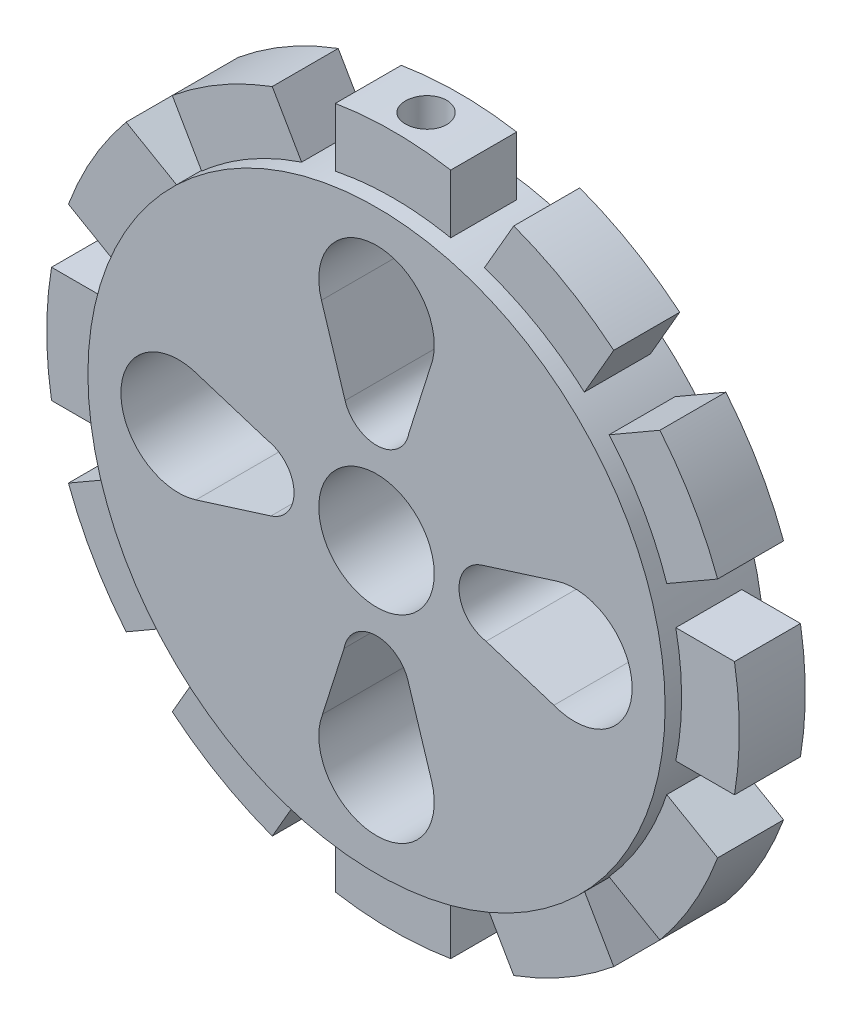
SolidWorks part; units mm, degrees
ref_plane "Alzado" through (0, 0, 0) normal (0, 0, 1) x (1, 0, 0)
ref_plane "Planta" through (0, 0, 0) normal (0, 1, 0) x (1, 0, 0)
ref_plane "Vista lateral" through (0, 0, 0) normal (1, 0, 0) x (0, 0, -1)
sketch "Croquis1" plane through (0, 0, 0) normal (0, 0, 1) x (1, 0, 0)
  line L0 (0, 50.5358) -> (0, -48.5678) construction
  line L1 (-51.7307, 0) -> (57.213, 0) construction
  line L2 (-6.6776, 21.9) -> (-3.8158, 12.8)
  line L3 (3.9355, 13.2848) -> (6.5412, 21.5075)
  line L4 (21.9, 6.6776) -> (12.8, 3.8158)
  line L5 (13.2848, -3.9355) -> (21.5075, -6.5412)
  line L6 (6.6776, -21.9) -> (3.8158, -12.8)
  line L7 (-3.9355, -13.2848) -> (-6.5412, -21.5075)
  line L8 (-21.9, -6.6776) -> (-12.8, -3.8158)
  line L9 (-13.2848, 3.9355) -> (-21.5075, 6.5412)
  circle A0 centre (0, 0) radius 7
  circle A1 centre (0, 0) radius 35
  arc A2 (-3.8158, 12.8) -> (3.9355, 13.2848) centre (0, 14) ccw
  arc A3 (6.5412, 21.5075) -> (-6.6776, 21.9) centre (0, 24) ccw
  arc A4 (21.5075, -6.5412) -> (21.9, 6.6776) centre (24, 0) ccw
  arc A5 (12.8, 3.8158) -> (13.2848, -3.9355) centre (14, 0) ccw
  arc A6 (-6.5412, -21.5075) -> (6.6776, -21.9) centre (0, -24) ccw
  arc A7 (3.8158, -12.8) -> (-3.9355, -13.2848) centre (0, -14) ccw
  arc A8 (-21.5075, 6.5412) -> (-21.9, -6.6776) centre (-24, 0) ccw
  arc A9 (-12.8, -3.8158) -> (-13.2848, 3.9355) centre (-14, 0) ccw
  point P43 (0, 0)
  dimension "D1" = 14
  dimension "D2" = 70
  dimension "D3" = 14
  dimension "D4" = 8
  dimension "D5" = 24
  dimension "D6" = 14
  dimension "D7" = 4
extrude "Saliente-Extruir1" add sketch "Croquis1" along normal mid plane 12
sketch "Croquis4" plane through (0, 0, 0) normal (0, 0, 1) x (1, 0, 0)
  line L0 (0, 73.6336) -> (0, -55.3664) construction
  line L1 (-7, 41.4126) -> (-7, 34.2929)
  line L2 (7, 41.4126) -> (7, 34.2929)
  line L3 (14.6441, 39.3643) -> (11.0843, 33.1985)
  line L4 (26.7685, 32.3643) -> (23.2086, 26.1985)
  line L5 (32.3643, 26.7685) -> (26.1985, 23.2086)
  line L6 (39.3643, 14.6441) -> (33.1985, 11.0843)
  line L7 (41.4126, 7) -> (34.2929, 7)
  line L8 (41.4126, -7) -> (34.2929, -7)
  line L9 (39.3643, -14.6441) -> (33.1985, -11.0843)
  line L10 (32.3643, -26.7685) -> (26.1985, -23.2086)
  line L11 (26.7685, -32.3643) -> (23.2086, -26.1985)
  line L12 (14.6441, -39.3643) -> (11.0843, -33.1985)
  line L13 (7, -41.4126) -> (7, -34.2929)
  line L14 (-7, -41.4126) -> (-7, -34.2929)
  line L15 (-14.6441, -39.3643) -> (-11.0843, -33.1985)
  line L16 (-26.7685, -32.3643) -> (-23.2086, -26.1985)
  line L17 (-32.3643, -26.7685) -> (-26.1985, -23.2086)
  line L18 (-39.3643, -14.6441) -> (-33.1985, -11.0843)
  line L19 (-41.4126, -7) -> (-34.2929, -7)
  line L20 (-41.4126, 7) -> (-34.2929, 7)
  line L21 (-39.3643, 14.6441) -> (-33.1985, 11.0843)
  line L22 (-32.3643, 26.7685) -> (-26.1985, 23.2086)
  line L23 (-26.7685, 32.3643) -> (-23.2086, 26.1985)
  line L24 (-14.6441, 39.3643) -> (-11.0843, 33.1985)
  arc A0 (7, 41.4126) -> (-7, 41.4126) centre (0, 0) ccw
  arc A1 (7, 34.2929) -> (-7, 34.2929) centre (0, 0) ccw
  arc A3 (23.2086, 26.1985) -> (11.0843, 33.1985) centre (0, 0) ccw
  arc A4 (26.7685, 32.3643) -> (14.6441, 39.3643) centre (0, 0) ccw
  arc A5 (33.1985, 11.0843) -> (26.1985, 23.2086) centre (0, 0) ccw
  arc A6 (39.3643, 14.6441) -> (32.3643, 26.7685) centre (0, 0) ccw
  arc A7 (34.2929, -7) -> (34.2929, 7) centre (0, 0) ccw
  arc A8 (41.4126, -7) -> (41.4126, 7) centre (0, 0) ccw
  arc A9 (26.1985, -23.2086) -> (33.1985, -11.0843) centre (0, 0) ccw
  arc A10 (32.3643, -26.7685) -> (39.3643, -14.6441) centre (0, 0) ccw
  arc A11 (11.0843, -33.1985) -> (23.2086, -26.1985) centre (0, 0) ccw
  arc A12 (14.6441, -39.3643) -> (26.7685, -32.3643) centre (0, 0) ccw
  arc A13 (-7, -34.2929) -> (7, -34.2929) centre (0, 0) ccw
  arc A14 (-7, -41.4126) -> (7, -41.4126) centre (0, 0) ccw
  arc A15 (-23.2086, -26.1985) -> (-11.0843, -33.1985) centre (0, 0) ccw
  arc A16 (-26.7685, -32.3643) -> (-14.6441, -39.3643) centre (0, 0) ccw
  arc A17 (-33.1985, -11.0843) -> (-26.1985, -23.2086) centre (0, 0) ccw
  arc A18 (-39.3643, -14.6441) -> (-32.3643, -26.7685) centre (0, 0) ccw
  arc A19 (-34.2929, 7) -> (-34.2929, -7) centre (0, 0) ccw
  arc A20 (-41.4126, 7) -> (-41.4126, -7) centre (0, 0) ccw
  arc A21 (-26.1985, 23.2086) -> (-33.1985, 11.0843) centre (0, 0) ccw
  arc A22 (-32.3643, 26.7685) -> (-39.3643, 14.6441) centre (0, 0) ccw
  arc A23 (-11.0843, 33.1985) -> (-23.2086, 26.1985) centre (0, 0) ccw
  arc A24 (-14.6441, 39.3643) -> (-26.7685, 32.3643) centre (0, 0) ccw
  point P55 (0, 0)
  dimension "D1" = 84
  dimension "D5" = 12
  dimension "D2" = 70
  dimension "D3" = 7
  dimension "D4" = 14
extrude "Saliente-Extruir2" add sketch "Croquis4" along normal mid plane 8 separate body
ref_plane "Plano3" through (0, 42, 0) normal (0, 1, 0) x (1, 0, 0)
sketch "Croquis7" plane through (0, 42, 0) normal (0, 1, 0) x (1, 0, 0)
  circle A0 centre (0, 0) radius 2.5
  dimension "D1" = 5
extrude "Cortar-Extruir3" cut sketch "Croquis7" against normal blind 4
